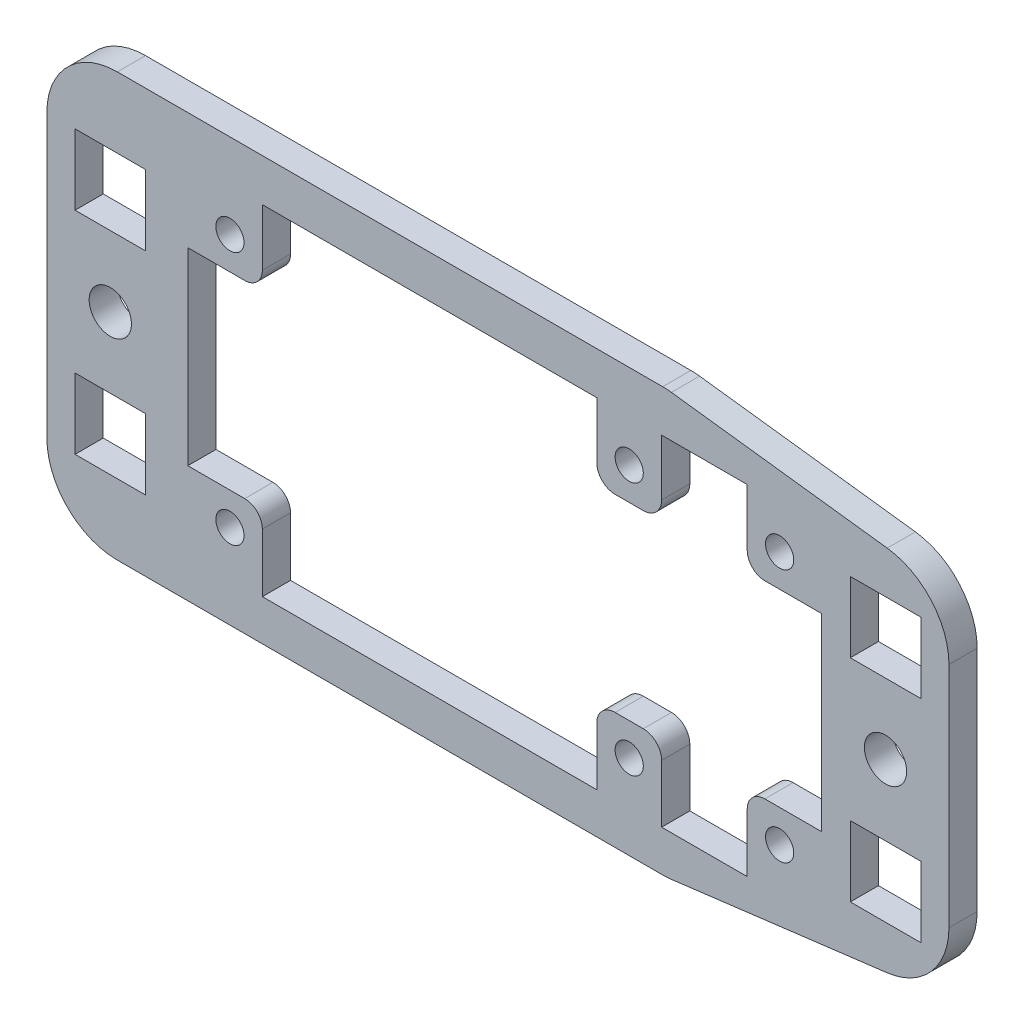
SolidWorks part; units mm, degrees
ref_plane "Plan de face" through (0, 0, 0) normal (0, 0, 1) x (1, 0, 0)
ref_plane "Plan de dessus" through (0, 0, 0) normal (0, 1, 0) x (1, 0, 0)
ref_plane "Plan de droite" through (0, 0, 0) normal (1, 0, 0) x (0, 0, -1)
sketch "Esquisse1" plane through (0, 0, 0) normal (0, 0, 1) x (1, 0, 0)
  line L0 (-10, 15) -> (54, 15) construction
  line L1 (54, 15) -> (54, -15) construction
  line L2 (54, -15) -> (-10, -15) construction
  line L3 (-10, -15) -> (-10, 15)
  line L4 (0, 0) -> (44.9752, 0) construction
  line L5 (-10, 15) -> (34, 15)
  line L6 (34, 15) -> (54, 12.5)
  line L7 (54, 12.5) -> (54, -12.5)
  line L8 (54, -12.5) -> (34, -15)
  line L9 (34, -15) -> (-10, -15)
  point P0 (0, 0)
  line B0 (28.5158, -12.1) -> (5.9876, -12.1) construction
  line B1 (0.2864, -6.7) -> (0.2984, -6.7)
  line B2 (5.2876, -7.95) -> (5.2876, -11.5) construction
  line B3 (0.2984, -6.7) -> (4.0376, -6.7) construction
  line B4 (0, -8) -> (0, 8) construction
  line B5 (44.6876, -6.7) -> (40.9376, -6.7) construction
  line B6 (39.6876, -7.95) -> (39.6876, -11.7) construction
  line B7 (44.9752, 8) -> (44.9752, -8) construction
  line B8 (4.0376, 6.7) -> (0, 6.7)
  line B9 (3.9876, 11.9876) -> (40.9876, 11.9876) construction
  line B10 (0, 6.7) -> (0, -6.7)
  line B11 (0, -6.7) -> (4.0376, -6.7)
  line B12 (39.6876, 7.95) -> (39.6876, 11.6999) construction
  line B13 (44.6876, 6.7) -> (40.9376, 6.7) construction
  line B14 (5.2876, -7.95) -> (5.2876, -12.1)
  line B15 (5.2876, -12.1) -> (29.0158, -12.1)
  line B16 (29.0158, -12.1) -> (29.0158, -8)
  line B17 (33.6158, -8) -> (33.6158, -12.1)
  line B18 (33.6158, -12.1) -> (39.6876, -12.1)
  line B19 (39.6876, -12.1) -> (39.6876, -7.95)
  line B20 (40.9376, -6.7) -> (44.9752, -6.7)
  line B21 (44.9752, -6.7) -> (44.9752, 6.7)
  line B22 (44.9752, 6.7) -> (40.9376, 6.7)
  line B23 (39.6876, 7.95) -> (39.6876, 11.9876)
  line B24 (39.6876, 11.9876) -> (33.6158, 11.9876)
  line B25 (33.6158, 11.9876) -> (33.6158, 8)
  line B26 (29.0158, 8) -> (29.0158, 11.9876)
  line B27 (29.0158, 11.9876) -> (5.2876, 11.9876)
  line B28 (5.2876, 11.9876) -> (5.2876, 7.95)
  line B29 (0.2984, 6.7) -> (0.2864, 6.6999)
  line B30 (4.0376, 6.7) -> (0.2984, 6.7) construction
  line B31 (5.2876, 11.4999) -> (5.2876, 7.95) construction
  line B32 (29.0158, 8) -> (29.0158, 11.6999) construction
  line B33 (33.6158, 11.6999) -> (33.6158, 8) construction
  line B34 (32.3158, 6.7) -> (30.3158, 6.7)
  line B35 (33.6158, -8) -> (33.6158, -11.7) construction
  line B36 (30.3158, -6.7) -> (32.3158, -6.7)
  line B37 (29.0158, -11.7) -> (29.0158, -8) construction
  arc B38 (5.2876, -7.95) -> (4.0376, -6.7) centre (4.0376, -7.95) ccw
  arc B39 (40.9376, -6.7) -> (39.6876, -7.95) centre (40.9376, -7.95) ccw
  arc B40 (31.3158, 10) -> (31.3158, 8) centre (31.3158, 9) ccw
  arc B41 (31.3158, 8) -> (31.3158, 10) centre (31.3158, 9) ccw
  arc B42 (39.6876, 7.95) -> (40.9376, 6.7) centre (40.9376, 7.95) ccw
  arc B43 (42.9876, 9) -> (40.9876, 9) centre (41.9876, 9) ccw
  arc B44 (40.9876, 9) -> (42.9876, 9) centre (41.9876, 9) ccw
  arc B45 (42.9876, -9) -> (40.9876, -9) centre (41.9876, -9) ccw
  arc B46 (40.9876, -9) -> (42.9876, -9) centre (41.9876, -9) ccw
  arc B47 (4.0376, 6.7) -> (5.2876, 7.95) centre (4.0376, 7.95) ccw
  arc B48 (31.3158, -8) -> (31.3158, -10) centre (31.3158, -9) ccw
  arc B49 (31.3158, -10) -> (31.3158, -8) centre (31.3158, -9) ccw
  arc B50 (32.3158, 6.7) -> (33.6158, 8) centre (32.3158, 8) ccw
  arc B51 (29.0158, 8) -> (30.3158, 6.7) centre (30.3158, 8) ccw
  arc B52 (33.6158, -8) -> (32.3158, -6.7) centre (32.3158, -8) ccw
  arc B53 (30.3158, -6.7) -> (29.0158, -8) centre (30.3158, -8) ccw
  arc B54 (1.9876, -9) -> (3.9876, -9) centre (2.9876, -9) ccw
  arc B55 (3.9876, -9) -> (1.9876, -9) centre (2.9876, -9) ccw
  arc B56 (1.9876, 9) -> (3.9876, 9) centre (2.9876, 9) ccw
  arc B57 (3.9876, 9) -> (1.9876, 9) centre (2.9876, 9) ccw
  line B58 (-5.5, 5) -> (-5.5, -5) construction
  line B59 (-8, 5) -> (-8, 10)
  line B60 (-8, 5) -> (-3, 5)
  line B61 (-3, 5) -> (-3, 10)
  line B62 (-8, 10) -> (-3, 10)
  line B63 (-8, -5) -> (-8, -10)
  line B64 (-8, -5) -> (-3, -5)
  line B65 (-3, -5) -> (-3, -10)
  line B66 (-8, -10) -> (-3, -10)
  line B67 (-5.5, 0) -> (-12.4724, 0) construction
  circle B68 centre (-5.5, 0) radius 1.5
  line B69 (49.5, 5) -> (49.5, -5) construction
  line B70 (47, 5) -> (47, 10)
  line B71 (47, 5) -> (52, 5)
  line B72 (52, 5) -> (52, 10)
  line B73 (47, 10) -> (52, 10)
  line B74 (47, -5) -> (47, -10)
  line B75 (47, -5) -> (52, -5)
  line B76 (52, -5) -> (52, -10)
  line B77 (47, -10) -> (52, -10)
  line B78 (49.5, 0) -> (42.5276, 0) construction
  circle B79 centre (49.5, 0) radius 1.5
  dimension "D1" = 30
  dimension "D2" = 2
  dimension "D3" = 3
  dimension "D4" = 20
  dimension "D5" = 2
  dimension "D6" = 50
  dimension "D7" = 25
sketch_block_instance "Block1-1"
sketch_block "Block1"
sketch_block_instance "Trou M3 plots 5mm-4"
sketch_block "Trou M3 plots 5mm" parameters "D2"=3, "D1"=5, "D3"=5, "D4"=10
sketch_block_instance "Trou M3 plots 5mm-5"
extrude "Boss.-Extru.1" add sketch "Esquisse1" along normal blind 2
fillet "Fillet1" radius 5 6 edges at (34, 15, 1) (-10, 15, 1) (-10, -15, 1) (34, -15, 1) (54, -12.5, 1) (54, 12.5, 1)
